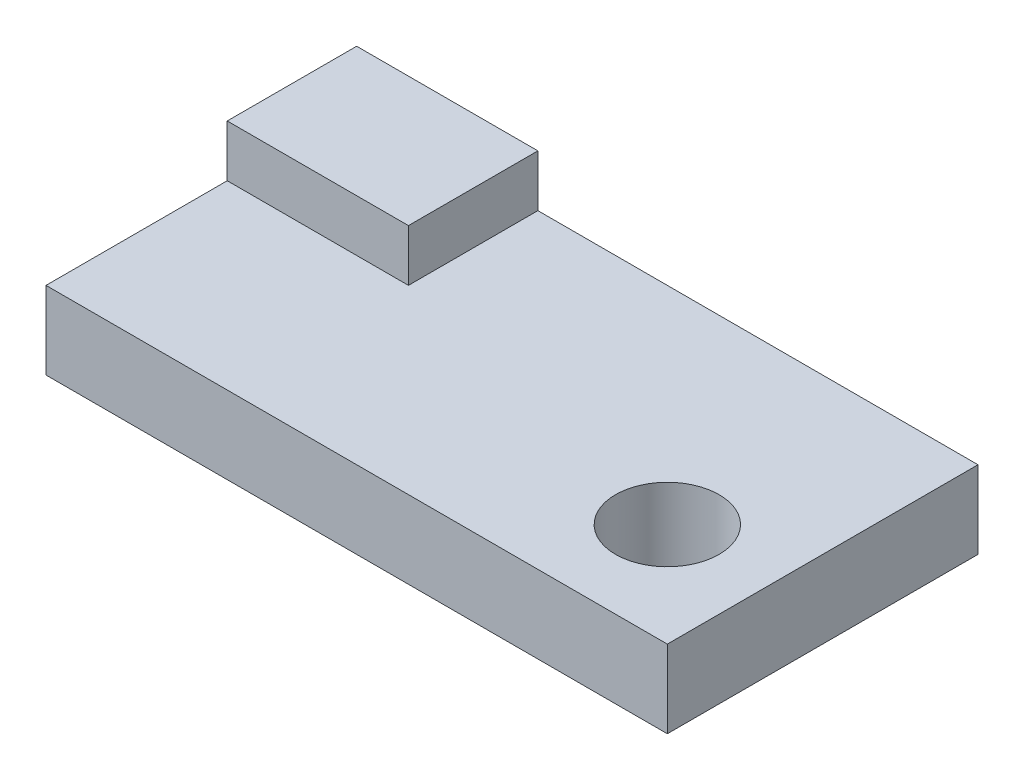
SolidWorks part; units mm, degrees
ref_plane "Alzado" through (0, 0, 0) normal (0, 0, 1) x (1, 0, 0)
ref_plane "Planta" through (0, 0, 0) normal (0, 1, 0) x (1, 0, 0)
ref_plane "Vista lateral" through (0, 0, 0) normal (1, 0, 0) x (0, 0, -1)
sketch "Croquis1" plane through (0, 0, 0) normal (0, 1, 0) x (1, 0, 0)
  line L1 (-60, 30) -> (60, 30)
  line L2 (-60, 30) -> (-60, -30)
  line L3 (-60, -30) -> (60, -30)
  line L4 (60, 30) -> (60, -30)
  circle A0 centre (40, -10) radius 10
  point P4 (-60, 0)
  point P5 (0, 30)
  dimension "D3" = 20
  dimension "D5" = 20
  dimension "D1" = 120
  dimension "D2" = 60
  dimension "D4" = 20
extrude "Saliente-Extruir1" add sketch "Croquis1" along normal blind 15
sketch "Croquis2" plane through (0, 15, 0) normal (0, 1, 0) x (1, 0, 0)
  line L1 (-60, 30) -> (-25, 30)
  line L2 (-60, 30) -> (-60, 5)
  line L3 (-60, 5) -> (-25, 5)
  line L4 (-25, 30) -> (-25, 5)
  dimension "D1" = 25
  dimension "D2" = 35
extrude "Saliente-Extruir2" add sketch "Croquis2" along normal blind 10
